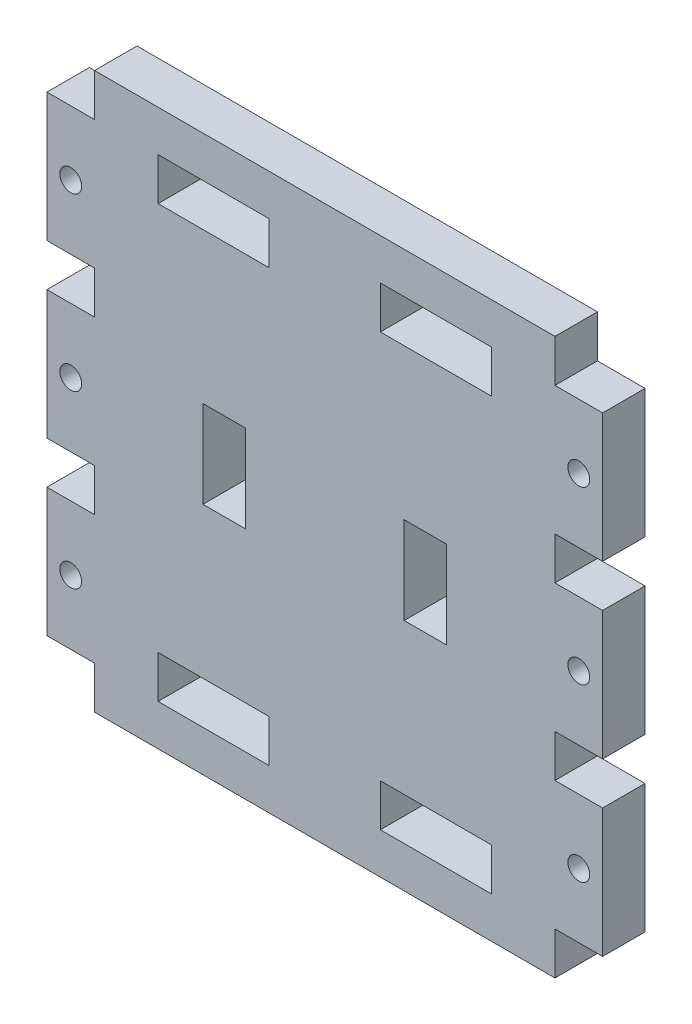
SolidWorks part; units mm, degrees
ref_plane "Front Plane" through (0, 0, 0) normal (0, 0, 1) x (1, 0, 0)
ref_plane "Top Plane" through (0, 0, 0) normal (0, 1, 0) x (1, 0, 0)
ref_plane "Right Plane" through (0, 0, 0) normal (1, 0, 0) x (0, 0, -1)
sketch "Model" plane through (0, 0, 0) normal (0, 0, 1) x (1, 0, 0)
  line L0 (29, 70) -> (29, 0) construction
  line L1 (0, 0) -> (58, 0)
  line L2 (0, 0) -> (0, 5.35)
  line L3 (0, 70) -> (58, 70)
  line L4 (58, 0) -> (58, 5.35)
  line L5 (58, 35) -> (-17.4057, 35) construction
  line L6 (-3, 64.65) -> (-3, 48.45) construction
  line L7 (8, 64.83) -> (22, 64.83)
  line L8 (8, 64.83) -> (8, 59.48)
  line L9 (8, 59.48) -> (22, 59.48)
  line L10 (22, 64.83) -> (22, 59.48)
  line L11 (0, 64.65) -> (-6, 64.65)
  line L12 (64, 56.55) -> (58, 56.55) construction
  line L13 (0, 48.45) -> (-6, 48.45)
  line L14 (-6, 64.65) -> (-6, 48.45)
  line L15 (-6, 56.55) -> (0, 56.55) construction
  line L16 (0, 64.65) -> (0, 70)
  line L17 (61, 64.65) -> (61, 48.45) construction
  line L18 (64, 64.65) -> (64, 48.45)
  line L19 (58, 48.45) -> (64, 48.45)
  line L20 (58, 64.65) -> (64, 64.65)
  line L21 (36, 64.83) -> (36, 59.48)
  line L22 (50, 59.48) -> (36, 59.48)
  line L23 (50, 64.83) -> (50, 59.48)
  line L24 (50, 64.83) -> (36, 64.83)
  line L25 (61, 5.35) -> (61, 21.55) construction
  line L26 (-6, 13.45) -> (0, 13.45) construction
  line L27 (64, 13.45) -> (58, 13.45) construction
  line L28 (-3, 5.35) -> (-3, 21.55) construction
  line L29 (50, 5.17) -> (36, 5.17)
  line L30 (50, 5.17) -> (50, 10.52)
  line L31 (50, 10.52) -> (36, 10.52)
  line L32 (36, 5.17) -> (36, 10.52)
  line L33 (58, 5.35) -> (64, 5.35)
  line L34 (58, 21.55) -> (64, 21.55)
  line L35 (64, 5.35) -> (64, 21.55)
  line L36 (-6, 5.35) -> (-6, 21.55)
  line L37 (0, 21.55) -> (-6, 21.55)
  line L38 (0, 5.35) -> (-6, 5.35)
  line L39 (22, 5.17) -> (22, 10.52)
  line L40 (8, 10.52) -> (22, 10.52)
  line L41 (8, 5.17) -> (8, 10.52)
  line L42 (8, 5.17) -> (22, 5.17)
  line L43 (0, 21.55) -> (0, 26.9)
  line L44 (58, 21.55) -> (58, 26.9)
  line L45 (58, 64.65) -> (58, 70)
  line L46 (-6, 35) -> (0, 35) construction
  line L47 (0, 43.1) -> (-6, 43.1)
  line L48 (44.35, 40.5) -> (39, 29.5) construction
  line L49 (0, 26.9) -> (-6, 26.9)
  line L50 (-6, 43.1) -> (-6, 26.9)
  line L51 (-3, 43.1) -> (-3, 26.9) construction
  line L52 (0, 43.1) -> (0, 48.45)
  line L53 (13.65, 29.5) -> (19, 29.5)
  line L54 (13.65, 29.5) -> (13.65, 40.5)
  line L55 (13.65, 40.5) -> (19, 40.5)
  line L56 (19, 29.5) -> (19, 40.5)
  line L57 (13.65, 29.5) -> (19, 40.5) construction
  line L58 (13.65, 40.5) -> (19, 29.5) construction
  line L59 (44.35, 29.5) -> (39, 40.5) construction
  line L60 (61, 43.1) -> (61, 26.9) construction
  line L61 (64, 35) -> (58, 35) construction
  line L62 (39, 29.5) -> (39, 40.5)
  line L63 (44.35, 40.5) -> (39, 40.5)
  line L64 (44.35, 29.5) -> (44.35, 40.5)
  line L65 (44.35, 29.5) -> (39, 29.5)
  line L66 (64, 43.1) -> (64, 26.9)
  line L67 (58, 26.9) -> (64, 26.9)
  line L68 (58, 43.1) -> (64, 43.1)
  line L69 (58, 43.1) -> (58, 48.45)
  circle A1 centre (-3, 56.55) radius 1.375
  circle A6 centre (61, 56.55) radius 1.375
  circle A7 centre (61, 13.45) radius 1.375
  circle A8 centre (-3, 13.45) radius 1.375
  circle A9 centre (-3, 35) radius 1.375
  circle A10 centre (61, 35) radius 1.375
  point P84 (16.325, 35)
  point P102 (41.675, 35)
  dimension "D23" = 2.75
  dimension "D2" = 58
  dimension "D6" = 70
  dimension "D8" = 5.35
  dimension "D10" = 14
  dimension "D12" = 5.17
  dimension "D14" = 8
  dimension "D19" = 5.35
  dimension "D22" = 5.35
  dimension "D24" = 6
  dimension "D25" = 16.2
  dimension "D26" = 5.35
  dimension "D27" = 11
  dimension "D30" = 13.65
extrude "Boss-Extrude1" add sketch "Model" along normal blind 5.35
equation "\"mdfthick\"=5.35"
equation "\"D26@Model\"=\"mdfthick\""
equation "\"D8@Model\"=\"mdfthick\""
equation "\"D19@Model\"=\"mdfthick\""
equation "\"D1@Boss-Extrude1\"=\"mdfthick\""
